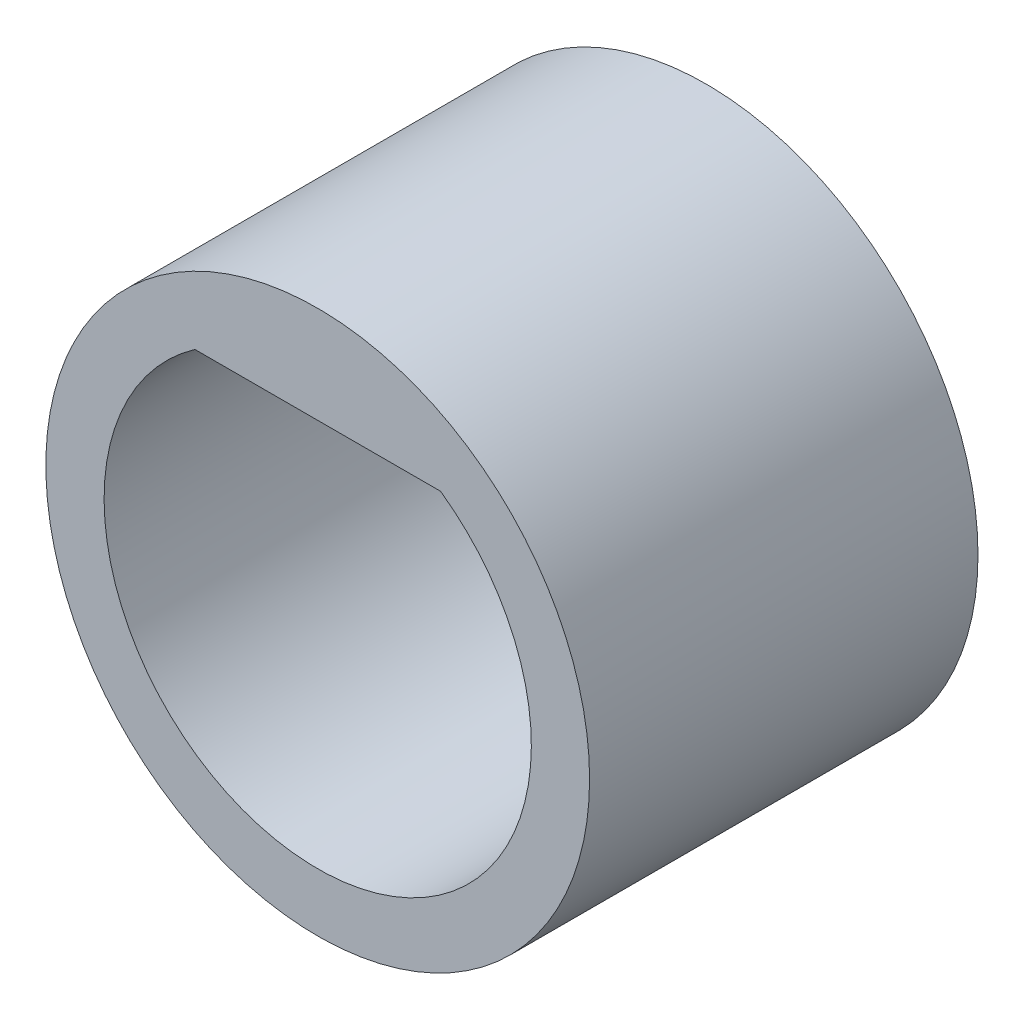
SolidWorks part; units mm, degrees
ref_plane "Front Plane" through (0, 0, 0) normal (0, 0, 1) x (1, 0, 0)
ref_plane "Top Plane" through (0, 0, 0) normal (0, 1, 0) x (1, 0, 0)
ref_plane "Right Plane" through (0, 0, 0) normal (1, 0, 0) x (0, 0, -1)
sketch "Sketch1" plane through (0, 0, 0) normal (0, 0, 1) x (1, 0, 0)
  line L0 (0, 0) -> (14.4477, 0) construction
  line L1 (7.2239, 0) -> (7.2239, 6.3746) construction
  line L2 (4.0616, 4.5) -> (11.2067, 4.5) construction
  line L3 (4.0616, 4.5) -> (10.3861, 4.5)
  arc A0 (4.0616, 4.5) -> (10.3861, 4.5) centre (7.2239, 0) ccw
  circle A1 centre (7.2239, 0) radius 7
  dimension "D1" = 4.5
  dimension "D2" = 11
extrude "Boss-Extrude2" add sketch "Sketch1" along normal blind 10
